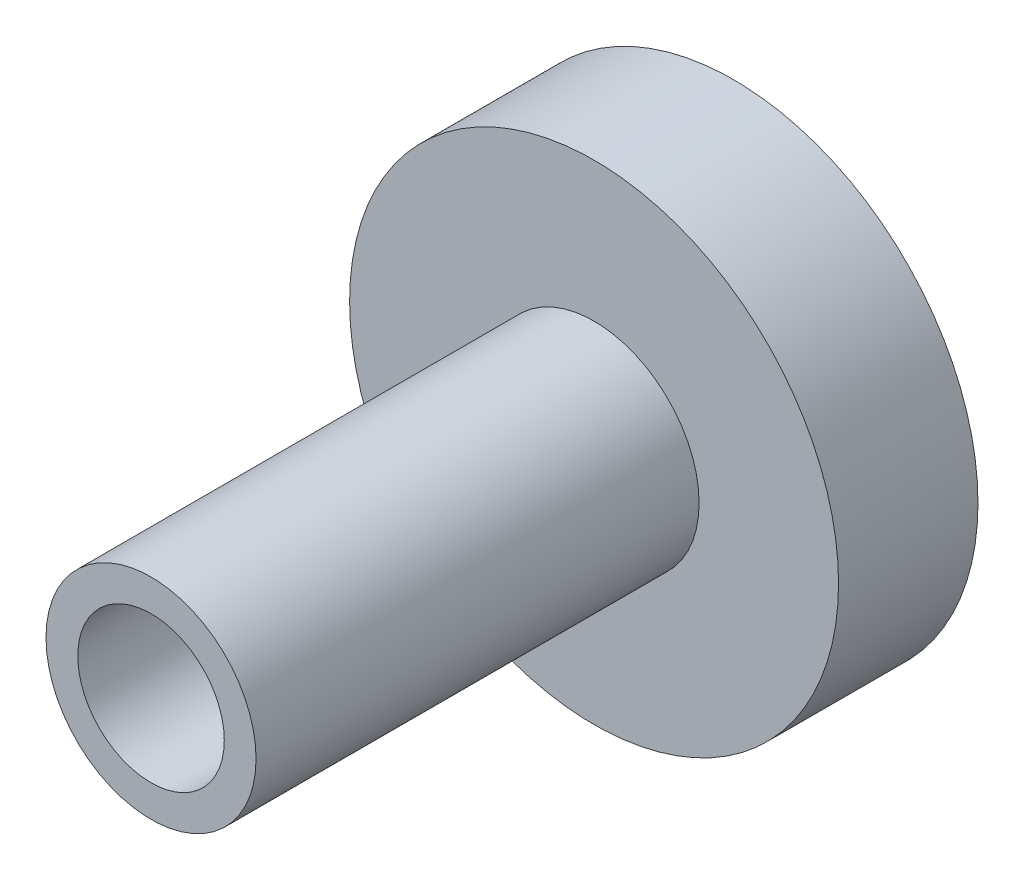
SolidWorks part; units mm, degrees
ref_plane "Front Plane" through (0, 0, 0) normal (0, 0, 1) x (1, 0, 0)
ref_plane "Top Plane" through (0, 0, 0) normal (0, 1, 0) x (1, 0, 0)
ref_plane "Right Plane" through (0, 0, 0) normal (1, 0, 0) x (0, 0, -1)
sketch "Sketch1" plane through (0, 0, 0) normal (0, 0, 1) x (1, 0, 0)
  circle A0 centre (0, 0) radius 13.85
  circle A1 centre (0, 0) radius 4.15
  dimension "D1" = 27.7
  dimension "D2" = 8.3
extrude "Boss-Extrude1" add sketch "Sketch1" along normal blind 33
sketch "Sketch2" plane through (0, 0, 33) normal (0, 0, 1) x (1, 0, 0)
  circle A0 centre (0, 0) radius 5.95
  circle A1 centre (0, 0) radius 13.85
  circle A2 centre (0, 0) radius 13.85 construction
  dimension "D1" = 11.9
extrude "Cut-Extrude1" cut sketch "Sketch2" against normal blind 25.1
